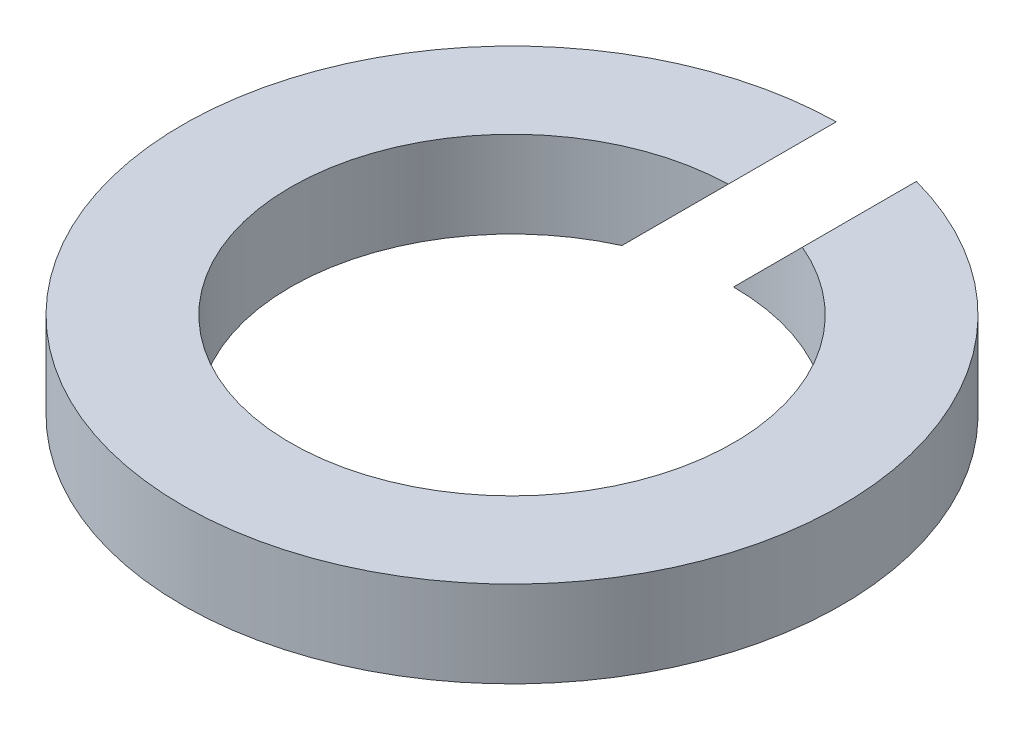
SolidWorks part; units mm, degrees
material "Простая углеродистая сталь"
ref_plane "Спереди" through (0, 0, 0) normal (0, 0, 1) x (1, 0, 0)
ref_plane "Сверху" through (0, 0, 0) normal (0, 1, 0) x (1, 0, 0)
ref_plane "Справа" through (0, 0, 0) normal (1, 0, 0) x (0, 0, -1)
sketch "Эскиз1" plane through (0, 0, 0) normal (0, 1, 0) x (1, 0, 0)
  circle A0 centre (0, 0) radius 4.1
  circle A1 centre (0, 0) radius 6.1
  dimension "d" = 8.2
  dimension "b" = 2
extrude "Бобышка-Вытянуть1" add sketch "Эскиз1" along normal blind 1.6
sketch "Эскиз2" plane through (0, 0, 0) normal (0, 0, 1) x (1, 0, 0)
  line L0 (0, 0) -> (1.6, 1.6)
  line L1 (1.6, 1.6) -> (-0.0971, 1.6)
  line L2 (-0.0971, 1.6) -> (-1.6971, 0)
  line L3 (-1.6971, 0) -> (0, 0)
  line L4 (6.1, 1.6) -> (-6.1, 1.6) construction
  line L5 (0, 0) -> (0, 4.5341) construction
  dimension "D1" = 45
  dimension "D2" = 1.2
extrude "Вырез-Вытянуть1" cut sketch "Эскиз2" against normal through all
equation "\"b,s\"=1.4"
equation "\"D2@Эскиз2\"=\"s@Бобышка-Вытянуть1\"*0.75"
